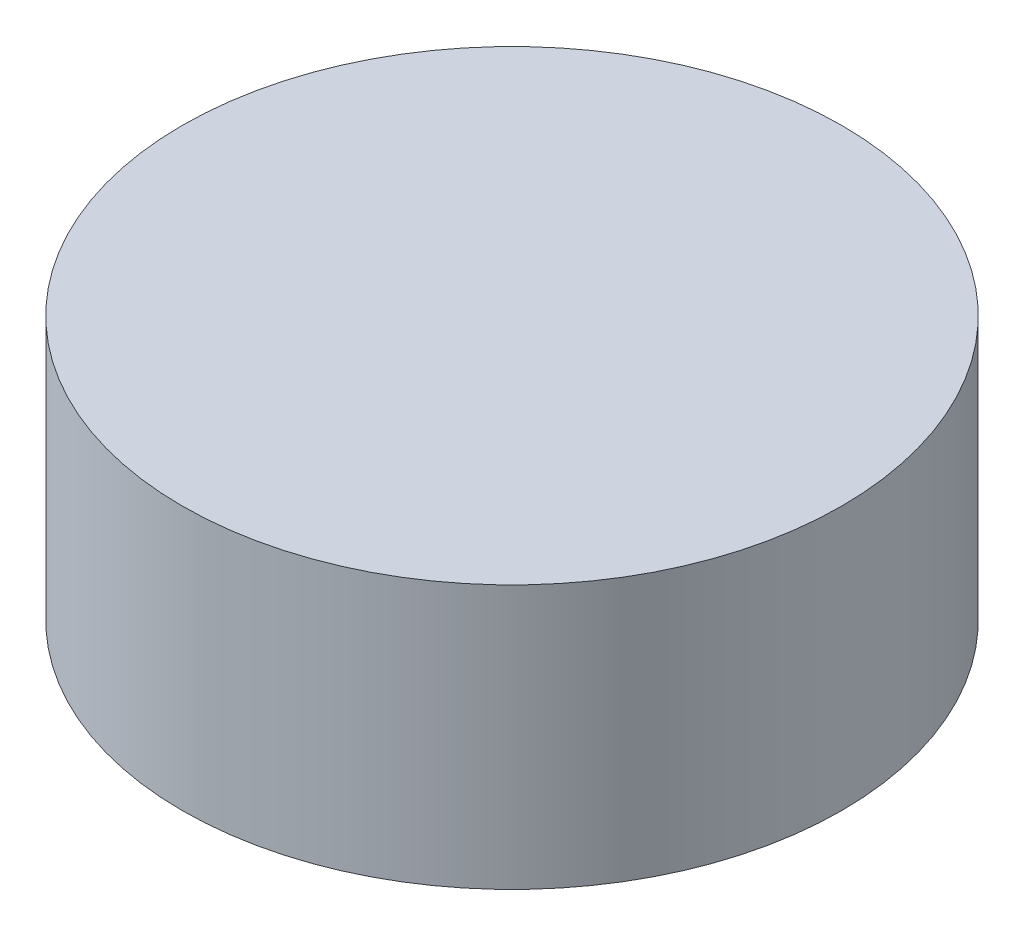
SolidWorks part; units mm, degrees
ref_plane "Front Plane" through (0, 0, 0) normal (0, 0, 1) x (1, 0, 0)
ref_plane "Top Plane" through (0, 0, 0) normal (0, 1, 0) x (1, 0, 0)
ref_plane "Right Plane" through (0, 0, 0) normal (1, 0, 0) x (0, 0, -1)
sketch "Sketch1" plane through (0, 0, 0) normal (0, 1, 0) x (1, 0, 0)
  circle A0 centre (0, 0) radius 7.9375
  dimension "D1" = 15.875
extrude "Boss-Extrude1" add sketch "Sketch1" along normal blind 6.35
